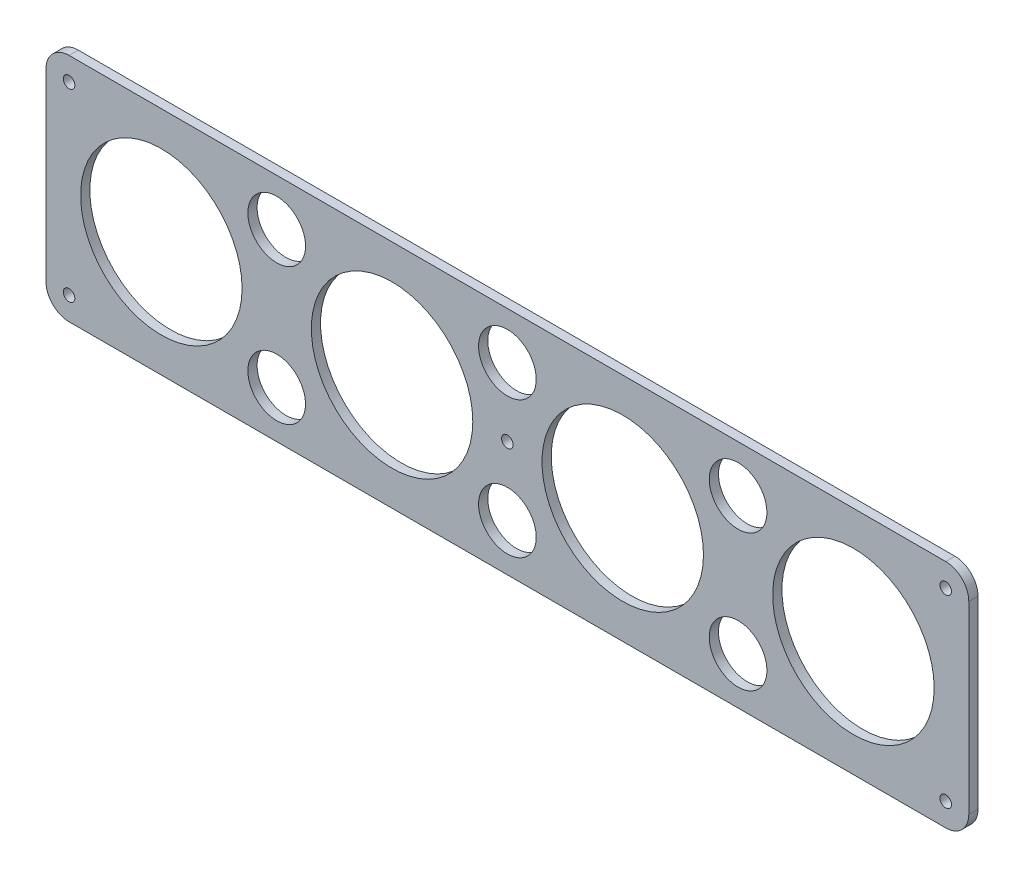
SolidWorks part; units mm, degrees
ref_plane "Front Plane" through (0, 0, 0) normal (0, 0, 1) x (1, 0, 0)
ref_plane "Top Plane" through (0, 0, 0) normal (0, 1, 0) x (1, 0, 0)
ref_plane "Right Plane" through (0, 0, 0) normal (1, 0, 0) x (0, 0, -1)
sketch "Sketch1" plane through (0, 0, 0) normal (0, 0, 1) x (1, 0, 0)
  line L0 (0, 50) -> (50, 50) construction
  line L1 (0, 0) -> (400, 0)
  line L2 (0, 0) -> (0, 100)
  line L3 (0, 100) -> (400, 100)
  line L4 (400, 100) -> (400, 0)
  line L5 (50, 50) -> (178.006, 50) construction
  line L6 (200, 0) -> (200, -47.1863) construction
  line L7 (100, 0) -> (100, -76.7417) construction
  circle A0 centre (50, 50) radius 35
  circle A1 centre (150, 50) radius 35
  circle A2 centre (250, 50) radius 35
  circle A3 centre (350, 50) radius 35
  circle A4 centre (100, 79.6423) radius 12.5
  circle A5 centre (100, 20.3577) radius 12.5
  circle A6 centre (200, 20.3577) radius 12.5
  circle A7 centre (200, 79.6423) radius 12.5
  circle A8 centre (300, 20.3577) radius 12.5
  circle A9 centre (300, 79.6423) radius 12.5
  circle A10 centre (10, 10) radius 2.5
  circle A11 centre (10, 90) radius 2.5
  circle A12 centre (390, 90) radius 2.5
  circle A13 centre (390, 10) radius 2.5
  circle A14 centre (200, 50) radius 2.5
  point P39 (100, -38.3708)
  dimension "D3" = 70
  dimension "D4" = 50
  dimension "D5" = 50
  dimension "D7" = 100
  dimension "D8" = 25
  dimension "D10" = 5
  dimension "D13" = 5
  dimension "D1" = 400
  dimension "D2" = 100
  dimension "D11" = 10
  dimension "D12" = 10
  dimension "D6" = 4
  dimension "D9" = 3
extrude "Boss-Extrude1" add sketch "Sketch1" along normal blind 4
fillet "Fillet1" radius 10 4 edges at (400, 100, 2) (400, 0, 2) (0, 0, 2) (0, 100, 2)
